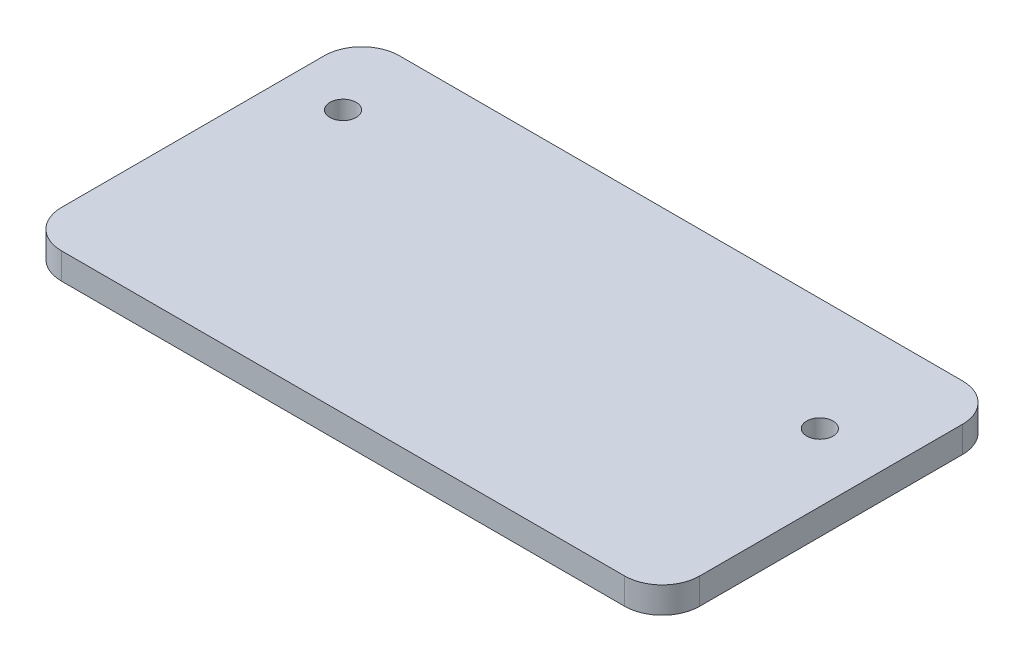
SolidWorks part; units mm, degrees
ref_plane "Alzado" through (0, 0, 0) normal (0, 0, 1) x (1, 0, 0)
ref_plane "Planta" through (0, 0, 0) normal (0, 1, 0) x (1, 0, 0)
ref_plane "Vista lateral" through (0, 0, 0) normal (1, 0, 0) x (0, 0, -1)
sketch "Croquis1" plane through (0, 0, 0) normal (0, 1, 0) x (1, 0, 0)
  line L1 (-37.5, 22.5) -> (37.5, 22.5)
  line L2 (-42.5, 17.5) -> (-42.5, -17.5)
  line L3 (-37.5, -22.5) -> (37.5, -22.5)
  line L4 (42.5, 17.5) -> (42.5, -17.5)
  line L5 (-42.5, 22.5) -> (42.5, -22.5) construction
  line L6 (-42.5, -22.5) -> (42.5, 22.5) construction
  circle A0 centre (-35, 12.5) radius 1.75
  circle A1 centre (33.5, 7.5) radius 1.75
  arc A2 (37.5, 22.5) -> (42.5, 17.5) centre (37.5, 17.5) cw
  arc A3 (42.5, -17.5) -> (37.5, -22.5) centre (37.5, -17.5) cw
  arc A4 (-37.5, -22.5) -> (-42.5, -17.5) centre (-37.5, -17.5) cw
  arc A5 (-42.5, 17.5) -> (-37.5, 22.5) centre (-37.5, 17.5) cw
  point P0 (0, 0)
  point P6 (-35, 12.5)
  point P7 (33.5, 7.5)
  dimension "D7" = 3.5
  dimension "D8" = 3.5
  dimension "D9" = 5
  dimension "D1" = 85
  dimension "D2" = 45
  dimension "D3" = 10
  dimension "D4" = 7.5
  dimension "D5" = 15
  dimension "D6" = 9
extrude "Saliente-Extruir1" add sketch "Croquis1" along normal blind 3.5 contours L2 A4 L3 A3 L4 A2 L1 A5 | A0 | A1
